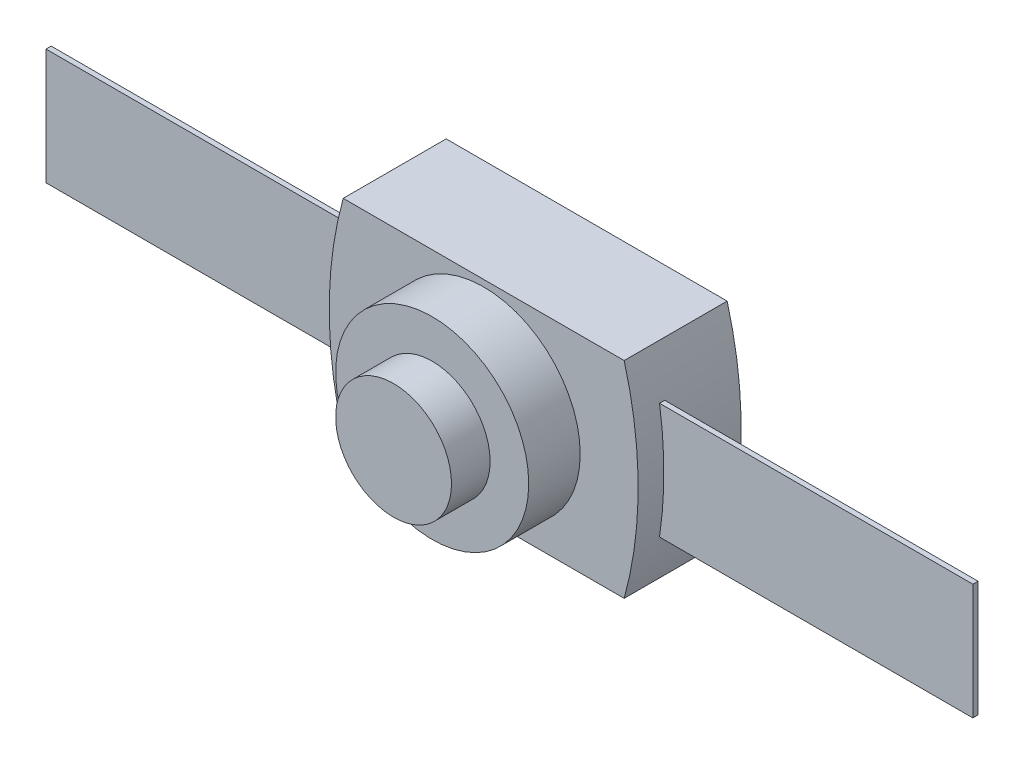
SolidWorks part; units mm, degrees
ref_plane "Спереди" through (0, 0, 0) normal (0, 0, 1) x (1, 0, 0)
ref_plane "Сверху" through (0, 0, 0) normal (0, 1, 0) x (1, 0, 0)
ref_plane "Справа" through (0, 0, 0) normal (1, 0, 0) x (0, 0, -1)
sketch "Эскиз1" plane through (0, 0, 0) normal (0, 0, 1) x (1, 0, 0)
  line L0 (6, 0) -> (6, -8) construction
  line L1 (0, 0) -> (12, 0)
  line L2 (0, 0) -> (0, -4)
  line L3 (0.5432, -8) -> (12, -8)
  line L4 (12, 0) -> (12, -8)
  arc A0 (0.5432, 0) -> (0.5432, -8) centre (15, -4) ccw
  arc A1 (11.4568, 0) -> (11.4568, -8) centre (-3, -4) cw
  dimension "D4" = 30
  dimension "D1" = 12
  dimension "D2" = 8
  dimension "D3" = 4
extrude "Бобышка-Вытянуть1" add sketch "Эскиз1" along normal blind 4 contours L1 L0 L3 A1 | L0 L1 A0 L3
sketch "Эскиз2" plane through (0, 0, 4) normal (0, 0, 1) x (1, 0, 0)
  line L0 (6, 0) -> (6, -8) construction
  line L1 (0.5432, 0) -> (11.4568, 0) construction
  line L2 (0.5432, -8) -> (11.4568, -8) construction
  line L3 (0, -4) -> (12, -4) construction
  arc A0 (0.5432, 0) -> (0.5432, -8) centre (15, -4) ccw construction
  arc A1 (11.4568, -8) -> (11.4568, 0) centre (-3, -4) ccw construction
  circle A2 centre (6, -4) radius 3.75
  dimension "D1" = 7.5
extrude "Бобышка-Вытянуть2" add sketch "Эскиз2" along normal blind 2
sketch "Эскиз3" plane through (0, 0, 6) normal (0, 0, 1) x (1, 0, 0)
  circle A0 centre (6, -4) radius 2.25
  dimension "D1" = 4.5
extrude "Бобышка-Вытянуть3" add sketch "Эскиз3" along normal blind 1.5
ref_plane "Плоскость4" through (0, 0, 3) normal (0, 0, -1) x (-1, 0, 0)
sketch "Эскиз4" plane through (0, 0, 3) normal (0, 0, -1) x (-1, 0, 0)
  line L0 (-0.5432, -8) -> (-11.4568, -8) construction
  line L1 (-24, -6.25) -> (12, -6.25)
  line L2 (-24, -6.25) -> (-24, -1.75)
  line L3 (-24, -1.75) -> (12, -1.75)
  line L4 (12, -6.25) -> (12, -1.75)
  circle A1 centre (-6, -4) radius 2.25 construction
  dimension "D1" = 36
  dimension "D2" = 1.75
  dimension "D3" = 4.5
  dimension "D4" = 18
extrude "Бобышка-Вытянуть4" add sketch "Эскиз4" along normal blind 0.2
